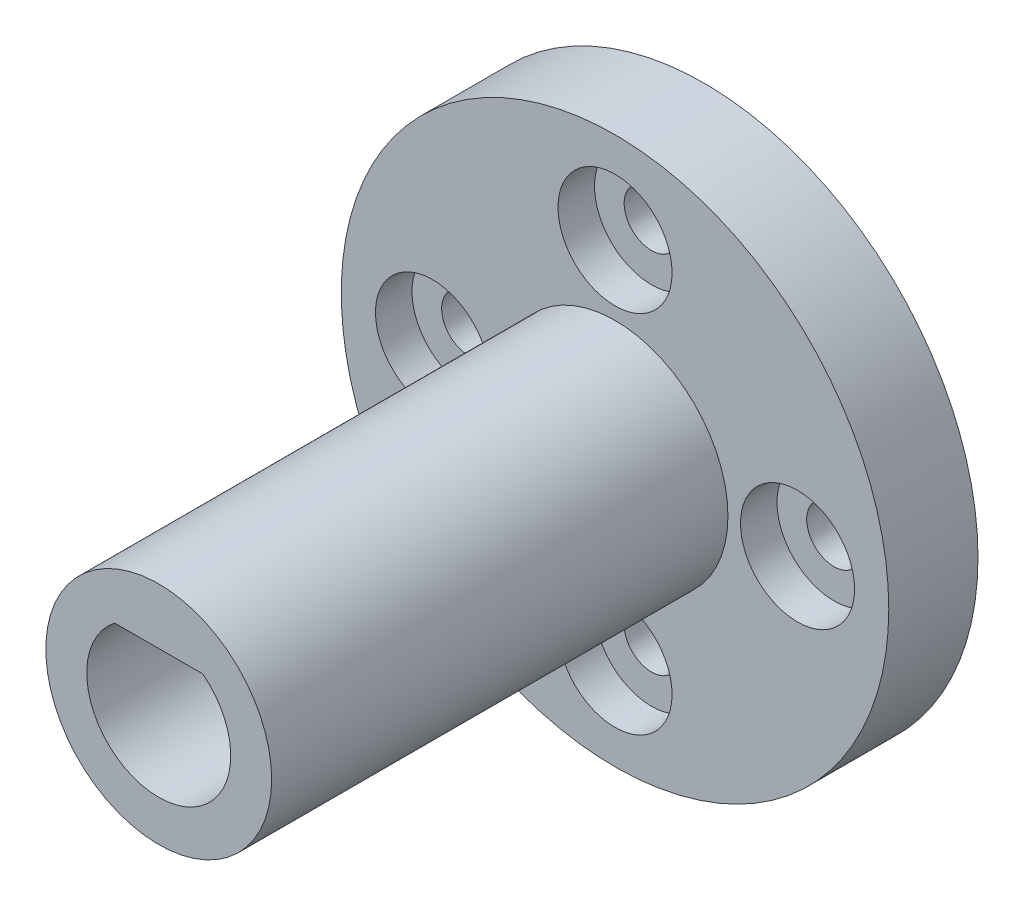
SolidWorks part; units mm, degrees
ref_plane "Plan de face" through (0, 0, 0) normal (0, 0, 1) x (1, 0, 0)
ref_plane "Plan de dessus" through (0, 0, 0) normal (0, 1, 0) x (1, 0, 0)
ref_plane "Plan de droite" through (0, 0, 0) normal (1, 0, 0) x (0, 0, -1)
sketch "Esquisse1" plane through (0, 0, 0) normal (0, 0, 1) x (1, 0, 0)
  circle A0 centre (0, 0) radius 12
  dimension "D1" = 24
extrude "Boss.-Extru.1" add sketch "Esquisse1" along normal blind 3.91
sketch "Esquisse6" plane through (0, 0, 0) normal (0, 0, -1) x (-1, 0, 0)
  circle A0 centre (0, 0) radius 4
  dimension "D1" = 8
extrude "Enlèv. mat.-Extru.2" cut sketch "Esquisse6" against normal blind 1.91
sketch "Esquisse7" plane through (0, 0, 3.91) normal (0, 0, 1) x (1, 0, 0)
  line L0 (1.9311, 2.495) -> (-1.9311, 2.495)
  line L1 (-5.4714, -3.155) -> (6.192, -3.155) construction
  arc A0 (-1.9311, 2.495) -> (1.9311, 2.495) centre (0, 0) ccw
  circle A1 centre (0, 0) radius 4.95
  dimension "D1" = 6.31
  dimension "D3" = 9.9
  dimension "D2" = 5.65
extrude "Boss.-Extru.2" add sketch "Esquisse7" along normal blind 20 contours A1 L1 A0 L0 | L1 A1
hole_wizard "Chambrage pour vis à tête ronde bombée M21" positions "Esquisse10" profile "Esquisse11" counterbore size "M2" standard "Ansi Metric" end condition through all
sketch "Esquisse10" plane through (0, 0, 3.91) normal (0, 0, 1) x (1, 0, 0)
  point P0 (0, 8)
  dimension "D1" = 8
sketch "Esquisse11" plane through (0, 8, 3.91) normal (1, 0, 0) x (0, -1, 0)
  line L0 (0, 0) -> (0, 3.91)
  line L1 (0, 3.91) -> (1.2, 3.91)
  line L3 (1.2, 3.91) -> (1.2, 1.6)
  line L4 (1.2, 1.6) -> (2.5, 1.6)
  line L5 (2.5, 1.6) -> (2.5, 0)
  line L7 (2.5, 0) -> (0, 0)
  line L11 (0, -6.35) -> (0, 107.95) construction
  dimension "Diamètre du perçage jusqu'au prochain" = 2.4
  dimension "Profondeur du perçage jusqu'au prochain" = 3.91
  dimension "Diamètre du chambrage" = 5
  dimension "Profondeur du chambrage" = 1.6
pattern_circular "Répétition circulaire2" count 4 every 90 about axis through (0, 0, 0) along (0, 0, 1) of "Chambrage pour vis à tête ronde bombée M21"
